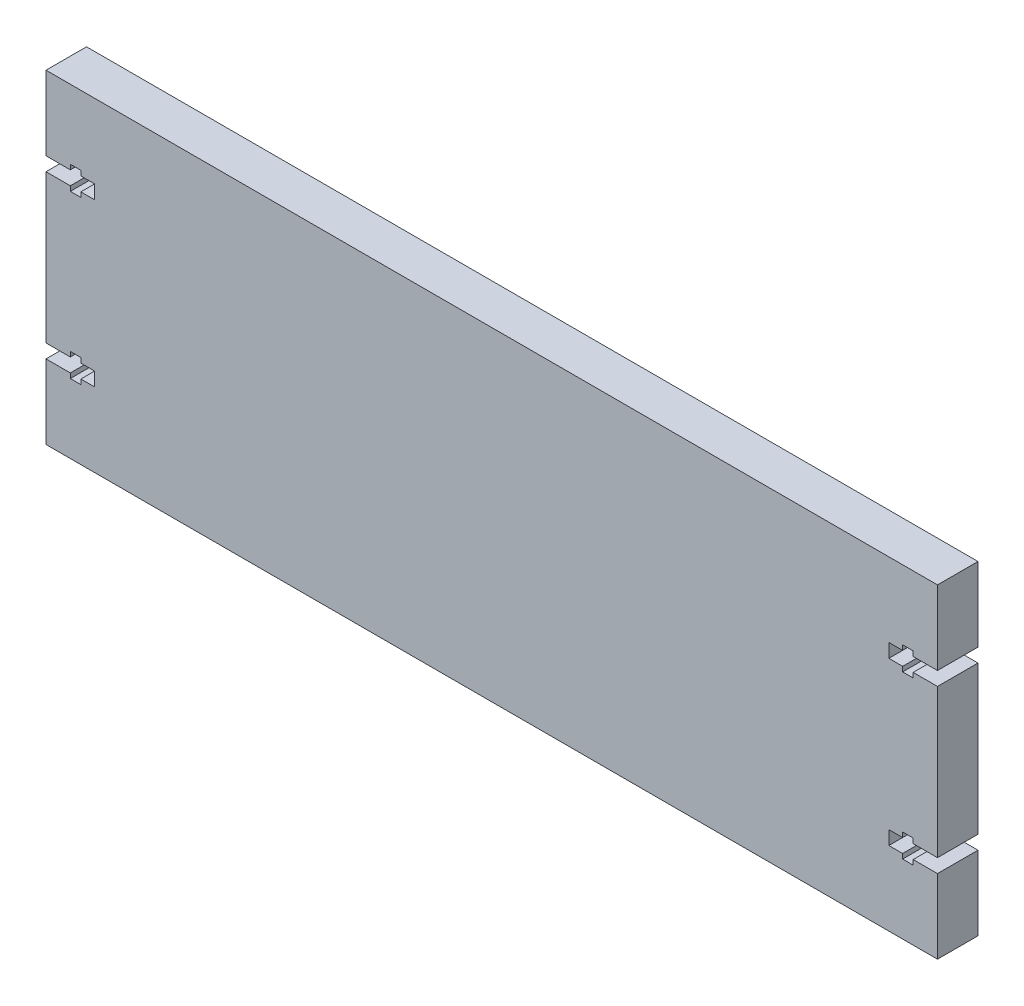
SolidWorks part; units mm, degrees
ref_plane "Front Plane" through (0, 0, 0) normal (0, 0, 1) x (1, 0, 0)
ref_plane "Top Plane" through (0, 0, 0) normal (0, 1, 0) x (1, 0, 0)
ref_plane "Right Plane" through (0, 0, 0) normal (1, 0, 0) x (0, 0, -1)
sketch "Sketch1" plane through (0, 0, 0) normal (0, 0, 1) x (1, 0, 0)
  line L1 (0, 0) -> (279.4, 0)
  line L2 (0, 0) -> (0, 101.6)
  line L3 (0, 101.6) -> (279.4, 101.6)
  line L4 (279.4, 0) -> (279.4, 101.6)
  dimension "D1" = 279.4
  dimension "D2" = 101.6
extrude "Boss-Extrude1" add sketch "Sketch1" along normal blind 12.7
sketch "Sketch2" plane through (0, 0, 12.7) normal (0, 0, 1) x (1, 0, 0)
  line L0 (279.4, 78.359) -> (279.4, 74.041)
  line L1 (279.4, 0) -> (279.4, 101.6) construction
  line L2 (279.4, 74.041) -> (271.78, 74.041)
  line L3 (271.78, 74.041) -> (271.78, 72.517)
  line L4 (271.78, 72.517) -> (268.478, 72.517)
  line L5 (268.478, 72.517) -> (268.478, 74.041)
  line L6 (268.478, 74.041) -> (264.16, 74.041)
  line L7 (264.16, 74.041) -> (264.16, 78.359)
  line L8 (264.16, 78.359) -> (268.478, 78.359)
  line L9 (268.478, 78.359) -> (268.478, 79.883)
  line L10 (268.478, 79.883) -> (271.78, 79.883)
  line L11 (271.78, 79.883) -> (271.78, 78.359)
  line L12 (271.78, 78.359) -> (279.4, 78.359)
  line L13 (279.4, 101.6) -> (0, 101.6) construction
  line L14 (139.7, 101.6) -> (139.7, 0) construction
  line L15 (0, 0) -> (279.4, 0) construction
  line L16 (0, 50.8) -> (279.4, 50.8) construction
  line L17 (0, 101.6) -> (0, 0) construction
  line L18 (271.78, 23.241) -> (279.4, 23.241)
  line L19 (271.78, 21.717) -> (271.78, 23.241)
  line L20 (268.478, 21.717) -> (271.78, 21.717)
  line L21 (268.478, 23.241) -> (268.478, 21.717)
  line L22 (264.16, 23.241) -> (268.478, 23.241)
  line L23 (264.16, 27.559) -> (264.16, 23.241)
  line L24 (268.478, 27.559) -> (264.16, 27.559)
  line L25 (268.478, 29.083) -> (268.478, 27.559)
  line L26 (271.78, 29.083) -> (268.478, 29.083)
  line L27 (271.78, 27.559) -> (271.78, 29.083)
  line L28 (279.4, 27.559) -> (271.78, 27.559)
  line L29 (279.4, 23.241) -> (279.4, 27.559)
  line L30 (0, 23.241) -> (0, 27.559)
  line L31 (0, 27.559) -> (7.62, 27.559)
  line L32 (7.62, 27.559) -> (7.62, 29.083)
  line L33 (7.62, 29.083) -> (10.922, 29.083)
  line L34 (10.922, 29.083) -> (10.922, 27.559)
  line L35 (10.922, 27.559) -> (15.24, 27.559)
  line L36 (15.24, 27.559) -> (15.24, 23.241)
  line L37 (15.24, 23.241) -> (10.922, 23.241)
  line L38 (10.922, 23.241) -> (10.922, 21.717)
  line L39 (10.922, 21.717) -> (7.62, 21.717)
  line L40 (7.62, 21.717) -> (7.62, 23.241)
  line L41 (7.62, 23.241) -> (0, 23.241)
  line L42 (7.62, 78.359) -> (0, 78.359)
  line L43 (7.62, 79.883) -> (7.62, 78.359)
  line L44 (10.922, 79.883) -> (7.62, 79.883)
  line L45 (10.922, 78.359) -> (10.922, 79.883)
  line L46 (15.24, 78.359) -> (10.922, 78.359)
  line L47 (15.24, 74.041) -> (15.24, 78.359)
  line L48 (10.922, 74.041) -> (15.24, 74.041)
  line L49 (10.922, 72.517) -> (10.922, 74.041)
  line L50 (7.62, 72.517) -> (10.922, 72.517)
  line L51 (7.62, 74.041) -> (7.62, 72.517)
  line L52 (0, 74.041) -> (7.62, 74.041)
  line L53 (0, 78.359) -> (0, 74.041)
  point P16 (279.4, 76.2)
  point P37 (279.4, 25.4)
  point P62 (0, 25.4)
  point P63 (0, 76.2)
  dimension "D1" = 15.24
  dimension "D2" = 3.302
  dimension "D3" = 4.318
  dimension "D4" = 7.366
  dimension "D5" = 7.62
  dimension "D6" = 25.4
extrude "Cut-Extrude1" cut sketch "Sketch2" against normal through all
